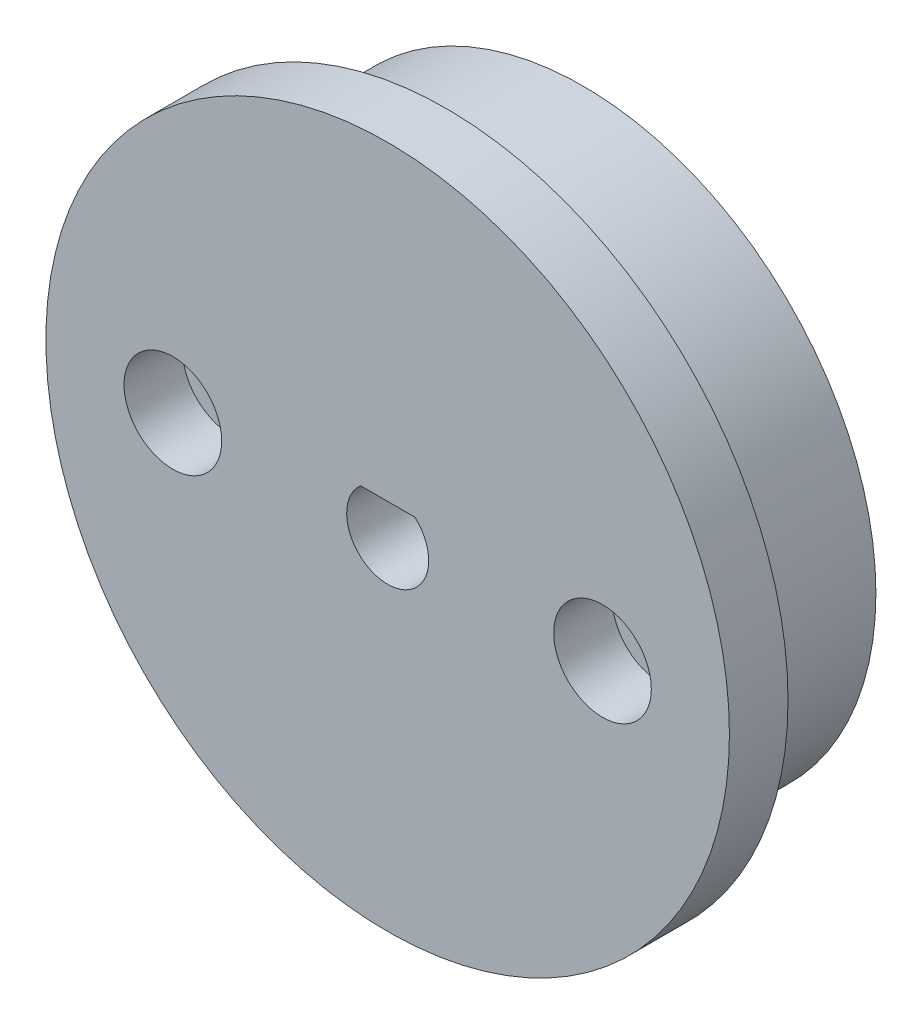
SolidWorks part; units mm, degrees
ref_plane "Front Plane" through (0, 0, 0) normal (0, 0, 1) x (1, 0, 0)
ref_plane "Top Plane" through (0, 0, 0) normal (0, 1, 0) x (1, 0, 0)
ref_plane "Right Plane" through (0, 0, 0) normal (1, 0, 0) x (0, 0, -1)
sketch "Sketch1" plane through (0, 0, 0) normal (0, 0, 1) x (1, 0, 0)
  circle A0 centre (0, 0) radius 15
  dimension "D1" = 30
extrude "Boss-Extrude1" add sketch "Sketch1" along normal blind 7
sketch "Sketch2" plane through (0, 0, 7) normal (0, 0, 1) x (1, 0, 0)
  circle A0 centre (0, 0) radius 17.5
  dimension "D1" = 35
extrude "Boss-Extrude2" add sketch "Sketch2" along normal blind 3
sketch "Sketch3" plane through (0, 0, 10) normal (0, 0, 1) x (1, 0, 0)
  circle A0 centre (-11, 0) radius 1.5
  circle A1 centre (11, 0) radius 1.5
  dimension "D3" = 3
  dimension "D4" = 3
  dimension "D1" = 11
  dimension "D2" = 11
  dimension "D5" = 22
extrude "Cut-Extrude1" cut sketch "Sketch3" against normal blind 10 contours A0 | A1
sketch "Sketch4" plane through (0, 0, 10) normal (0, 0, 1) x (1, 0, 0)
  line L0 (-1.389, 1.575) -> (1.389, 1.575)
  arc A2 (-1.389, 1.575) -> (1.389, 1.575) centre (0, 0) ccw
  dimension "D1" = 4.2
sketch "Sketch5" plane through (0, 0, 10) normal (0, 0, 1) x (1, 0, 0)
  circle A0 centre (11, 0) radius 2.5
  circle A1 centre (-11, 0) radius 2.5
  dimension "D1" = 5
  dimension "D2" = 5
extrude "Cut-Extrude3" cut sketch "Sketch5" against normal blind 3
extrude "Cut-Extrude5" cut sketch "Sketch4" against normal blind 10
